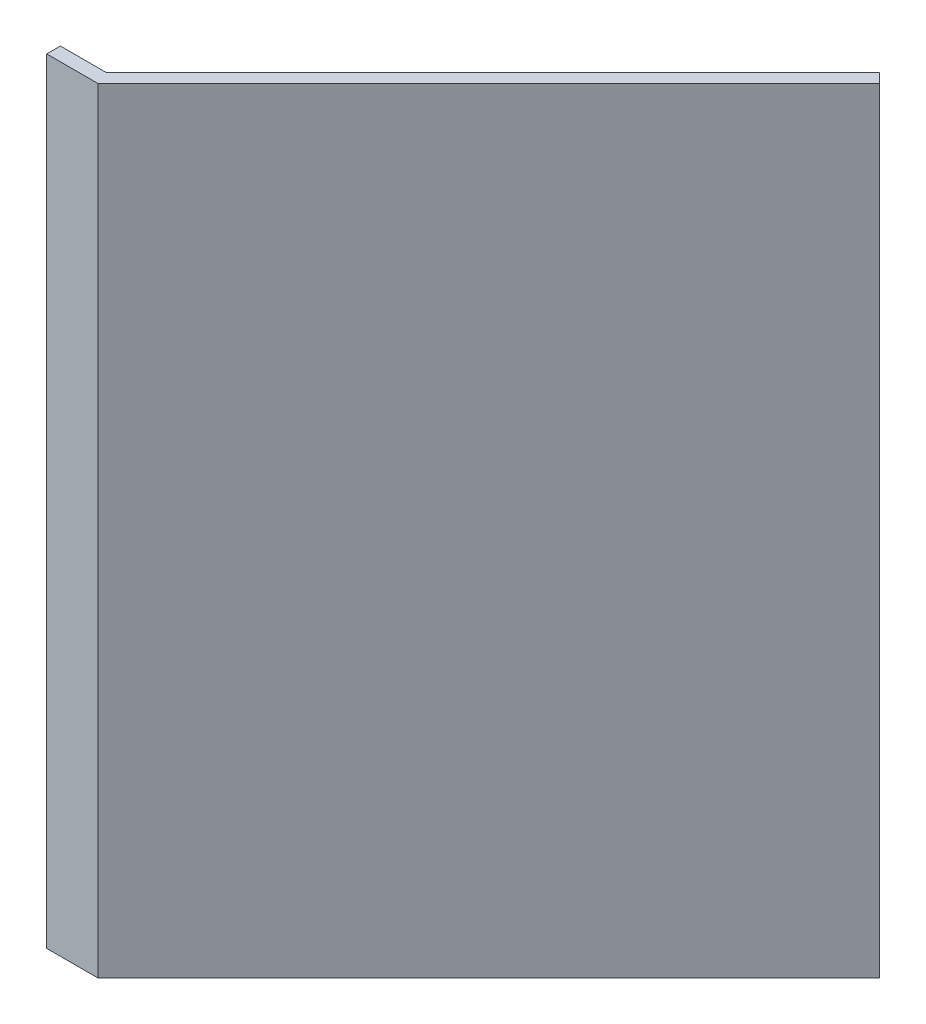
SolidWorks part; units mm, degrees
ref_plane "Front Plane" through (0, 0, 0) normal (0, 0, 1) x (1, 0, 0)
ref_plane "Top Plane" through (0, 0, 0) normal (0, 1, 0) x (1, 0, 0)
ref_plane "Right Plane" through (0, 0, 0) normal (1, 0, 0) x (0, 0, -1)
other "Configuration Table"
sketch "草图1" plane through (0, 0, 0) normal (0, 1, 0) x (1, 0, 0)
  line L0 (-70.8513, -74.7092) -> (14.0015, 10.1436)
  line L1 (-80.8513, -77.7092) -> (-70.8513, -77.7092)
  line L2 (-80.8513, -77.7092) -> (-80.8513, -74.7092)
  line L3 (-80.8513, -74.7092) -> (-70.8513, -74.7092)
  line L4 (-70.8513, -77.7092) -> (-70.8513, -74.7092)
  line L5 (14.0015, 10.1436) -> (16.1228, 8.0223)
  line L6 (16.1228, 8.0223) -> (-69.6087, -77.7092)
  line L7 (-69.6087, -77.7092) -> (-70.8513, -77.7092)
  dimension "D1" = 10
  dimension "D2" = 135
  dimension "3.2" = 3
  dimension "D3" = 120
  dimension "D4" = 3
extrude "凸台-拉伸1" add sketch "草图1" along normal blind 170 contours L7 L6 L5 L0 L4 | L1 L4 L3 L2
